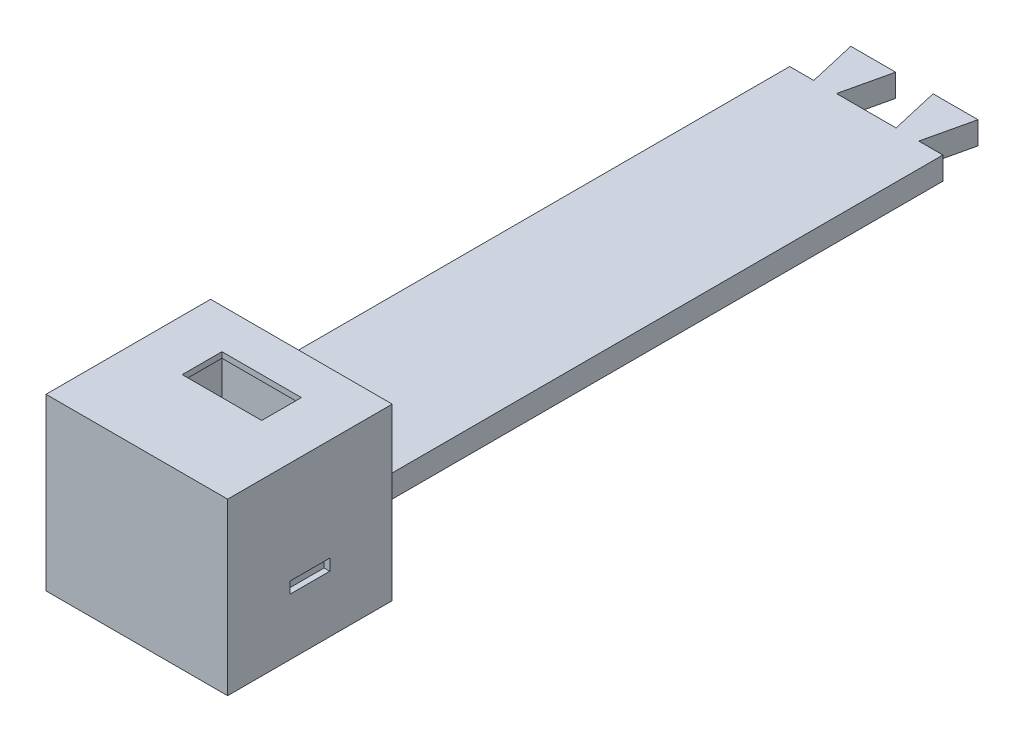
SolidWorks part; units mm, degrees
ref_plane "Plan de face" through (0, 0, 0) normal (0, 0, 1) x (1, 0, 0)
ref_plane "Plan de dessus" through (0, 0, 0) normal (0, 1, 0) x (1, 0, 0)
ref_plane "Plan de droite" through (0, 0, 0) normal (1, 0, 0) x (0, 0, -1)
sketch "Esquisse1" plane through (0, 0, 0) normal (0, 0, 1) x (1, 0, 0)
  line L1 (-13.5, -2) -> (13.5, -2)
  line L2 (-13.5, -2) -> (-13.5, 2)
  line L3 (-13.5, 2) -> (13.5, 2)
  line L4 (13.5, -2) -> (13.5, 2)
  line L5 (-13.5, -2) -> (13.5, 2) construction
  line L6 (-13.5, 2) -> (13.5, -2) construction
  point P0 (0, 0)
  dimension "D1" = 27
  dimension "D2" = 4
extrude "Boss.-Extru.1" add sketch "Esquisse1" along normal blind 108
sketch "Esquisse2" plane through (0, 0, 108) normal (0, 0, 1) x (1, 0, 0)
  line L1 (-16, -15) -> (16, -15)
  line L2 (-16, -15) -> (-16, 15)
  line L3 (-16, 15) -> (16, 15)
  line L4 (16, -15) -> (16, 15)
  line L5 (-16, -15) -> (16, 15) construction
  line L6 (-16, 15) -> (16, -15) construction
  point P0 (0, 0)
  dimension "D1" = 32
  dimension "D2" = 30
sketch "Esquisse8" plane through (0, 2, 0) normal (0, 1, 0) x (1, 0, 0)
  line L0 (-13.5, 0) -> (-11.2071, 0) construction
  line L1 (13.5, 0) -> (-13.5, 0) construction
  line L2 (-11.2071, 0) -> (-11.2071, -8.477) construction
  line L3 (-13.5, -8.477) -> (-9.25, -8.477) construction
  line L4 (-13.5, -108) -> (-13.5, 0) construction
  line L5 (-11.2071, 0) -> (-9.25, -8.477)
  line L6 (-9.25, -8.477) -> (-5.25, -8.477)
  line L7 (-5.25, -8.477) -> (-3.2929, 0)
  line L8 (-11.2071, 0) -> (-3.2929, 0) construction
  line L9 (-3.2929, 0) -> (3.2929, 0)
  line L10 (-3.2929, 0) -> (3.2929, 0) construction
  line L11 (3.2929, 0) -> (5.25, -8.477)
  line L12 (5.25, -8.477) -> (9.25, -8.477)
  line L13 (9.25, -8.477) -> (11.2071, 0)
  line L14 (3.2929, 0) -> (11.2071, 0) construction
  line L15 (-11.2071, 0) -> (-3.2929, 0) construction
  line L16 (3.2929, 0) -> (11.2071, 0) construction
  line L17 (-7.25, -8.477) -> (7.25, -8.477) construction
  line L18 (5.25, -8.477) -> (-5.25, -8.477)
  dimension "D1" = 26
  dimension "D2" = 26
  dimension "D3" = 14.5
  dimension "D4" = 4
  dimension "D5" = 4
  dimension "D6" = 8.7
  dimension "D7" = 8.7
  dimension "D8" = 8.7
  dimension "D9" = 8.7
  dimension "D10" = 4.25
  dimension "D12" = 7.9141
  dimension "D13" = 7.9141
sketch "Esquisse9" plane through (0, 2, 0) normal (0, 1, 0) x (1, 0, 0)
  line L0 (-3.2929, 0) -> (-5.25, -8.477)
  line L1 (-5.25, -8.477) -> (5.25, -8.477)
  line L2 (5.25, -8.477) -> (3.2929, 0)
  line L3 (3.2929, 0) -> (-3.2929, 0)
sketch "Esquisse10" plane through (0, 2, 0) normal (0, 1, 0) x (1, 0, 0)
  line L0 (-11.2071, 0) -> (-9.25, -8.477)
  line L1 (-9.25, -8.477) -> (-13.5, -8.477)
  line L2 (-13.5, -8.477) -> (-13.5, 0)
  line L3 (-13.5, 0) -> (-11.2071, 0)
  line L4 (11.2071, 0) -> (9.25, -8.477)
  line L5 (9.25, -8.477) -> (13.5, -8.477)
  line L6 (13.5, -108) -> (13.5, 0) construction
  line L7 (13.5, -8.477) -> (13.5, 0)
  line L8 (13.5, 0) -> (11.2071, 0)
sketch "Esquisse11" plane through (0, 2, 0) normal (0, 1, 0) x (1, 0, 0)
  line L0 (-11.2071, 0) -> (-9.25, -8.477)
  line L1 (-9.25, -8.477) -> (-13.5, -8.477)
  line L2 (-13.5, -8.477) -> (-13.5, 0)
  line L3 (-13.5, 0) -> (-11.2071, 0)
  line L4 (-3.2929, 0) -> (-5.25, -8.477)
  line L5 (-5.25, -8.477) -> (5.25, -8.477)
  line L6 (5.25, -8.477) -> (3.2929, 0)
  line L7 (3.2929, 0) -> (-3.2929, 0)
  line L8 (11.2071, 0) -> (9.25, -8.477)
  line L9 (9.25, -8.477) -> (13.5, -8.477)
  line L10 (13.5, -8.477) -> (13.5, 0)
  line L11 (13.5, 0) -> (11.2071, 0)
sketch "Esquisse12" plane through (0, 2, 0) normal (0, 1, 0) x (1, 0, 0)
  line L0 (-13.5, 0) -> (-11.2071, 0)
  line L1 (-11.2071, 0) -> (-9.25, -8.477)
  line L2 (-9.25, -8.477) -> (-13.5, -8.477)
  line L3 (-13.5, -8.477) -> (-13.5, 0)
  line L5 (-3.2929, 0) -> (-5.25, -8.477)
  line L6 (-5.25, -8.477) -> (5.25, -8.477)
  line L7 (5.25, -8.477) -> (3.2929, 0)
  line L8 (3.2929, 0) -> (-3.2929, 0)
  line L9 (11.2071, 0) -> (9.25, -8.477)
  line L10 (9.25, -8.477) -> (13.5, -8.477)
  line L11 (13.5, -8.477) -> (13.5, 0)
  line L12 (13.5, 0) -> (11.2071, 0)
extrude "Enlèv. mat.-Extru.3" cut sketch "Esquisse12" against normal through all
extrude "Boss.-Extru.2" add sketch "Esquisse2" along normal blind 29
sketch "Esquisse14" plane through (0, 15, 0) normal (0, 1, 0) x (1, 0, 0)
sketch "Esquisse17" plane through (0, -15, 0) normal (0, -1, 0) x (1, 0, 0)
  line L0 (0, 137) -> (0, 108) construction
  line L1 (-16, 137) -> (16, 137) construction
  line L2 (-13.5, 108) -> (13.5, 108) construction
  line L4 (-13.5, 108.5) -> (13.5, 108.5)
  line L5 (-13.5, 108.5) -> (-13.5, 136.5)
  line L6 (-13.5, 136.5) -> (13.5, 136.5)
  line L7 (13.5, 108.5) -> (13.5, 136.5)
  line L8 (-13.5, 108.5) -> (13.5, 136.5) construction
  line L9 (-13.5, 136.5) -> (13.5, 108.5) construction
  point P6 (0, 122.5)
  dimension "D1" = 28
  dimension "D2" = 27
extrude "Enlèv. mat.-Extru.4" cut sketch "Esquisse17" against normal blind 29
sketch "Esquisse18" plane through (16, 0, 0) normal (1, 0, 0) x (0, 0, -1)
  line L0 (-137, -5) -> (-126, -5) construction
  line L1 (-137, -15) -> (-137, 15) construction
  line L2 (-108, -5) -> (-119, -5) construction
  line L4 (-108, -15) -> (-108, 15) construction
  line L5 (-126, -15) -> (-126, -5) construction
  line L6 (-137, -15) -> (-108, -15) construction
  line L7 (-126, -5) -> (-119, -5)
  line L8 (-126, -5) -> (-126, -3)
  line L9 (-126, -3) -> (-119, -3)
  line L10 (-119, -3) -> (-119, -5)
extrude "Enlèv. mat.-Extru.6" cut sketch "Esquisse18" against normal blind 1
sketch "Esquisse24" plane through (-16, 0, 0) normal (-1, 0, 0) x (0, 0, 1)
  line L0 (137, 15) -> (137, -15) construction
  line L2 (108, 15) -> (108, -15) construction
  line L4 (126, -3) -> (126, -5)
  line L5 (126, -5) -> (119, -5)
  line L6 (119, -5) -> (119, -3)
  line L7 (119, -3) -> (126, -3)
  dimension "D1" = 2
  dimension "D2" = 11
  dimension "D3" = 11
sketch "Esquisse25" plane through (16, 0, 0) normal (1, 0, 0) x (0, 0, -1)
extrude "Enlèv. mat.-Extru.7" cut sketch "Esquisse24" against normal blind 1
sketch "Esquisse26" plane through (0, 14, 0) normal (0, -1, 0) x (1, 0, 0)
  line L0 (0, 108.5) -> (0, 121.5) construction
  line L1 (-13.5, 108.5) -> (13.5, 108.5) construction
  line L4 (7, 122) -> (7, 115)
  line L5 (7, 115) -> (-7, 115)
  line L6 (-7, 115) -> (-7, 122)
  line L7 (-7, 122) -> (7, 122)
  line L8 (13.5, 136.5) -> (-13.5, 136.5) construction
  dimension "D1" = 7
  dimension "D2" = 14.5
extrude "Enlèv. mat.-Extru.8" cut sketch "Esquisse26" against normal through all
